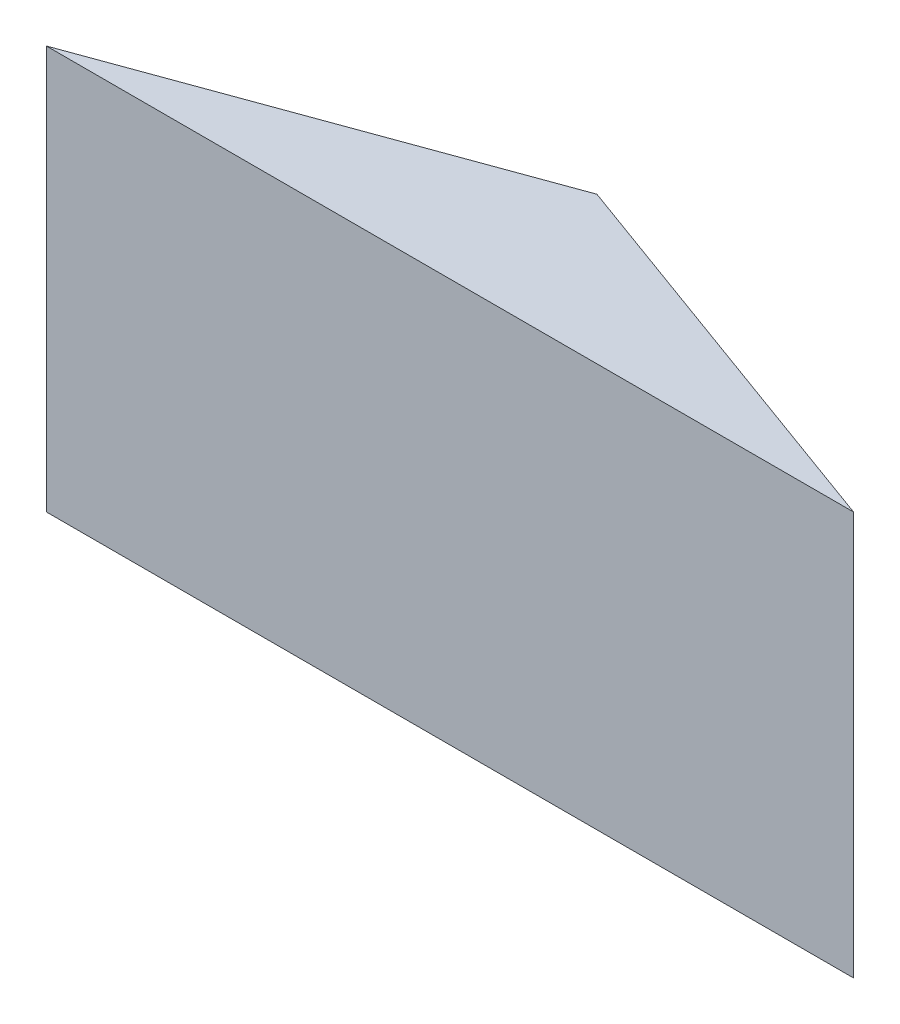
SolidWorks part; units mm, degrees
ref_plane "Přední rovina" through (0, 0, 0) normal (0, 0, 1) x (1, 0, 0)
ref_plane "Horní rovina" through (0, 0, 0) normal (0, 1, 0) x (1, 0, 0)
ref_plane "Pravá rovina" through (0, 0, 0) normal (1, 0, 0) x (0, 0, -1)
sketch "Sketch1" plane through (0, 0, 0) normal (0, 1, 0) x (1, 0, 0)
  line L0 (-20, 0) -> (20, 0)
  line L1 (20, 0) -> (0, 7.2794)
  line L2 (0, 7.2794) -> (0, 0) construction
  line L3 (-20, 0) -> (0, 7.2794)
  point P4 (0, 0)
  point P5 (0, 0)
  point P6 (0, 16.8591)
  dimension "D1" = 20
  dimension "D2" = 20
extrude "Boss-Extrude1" add sketch "Sketch1" along normal blind 20 contours L2 L3 L0 | L1 L2 L0
equation "\"ěé\"=30"
